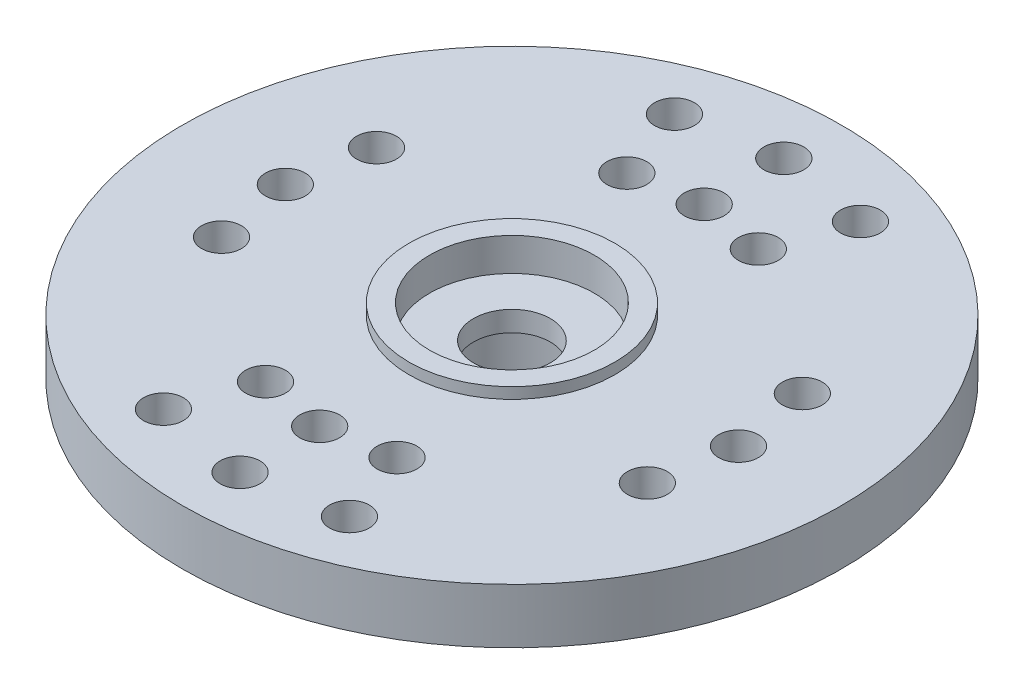
SolidWorks part; units mm, degrees
ref_plane "Front Plane" through (0, 0, 0) normal (0, 0, 1) x (1, 0, 0)
ref_plane "Top Plane" through (0, 0, 0) normal (0, 1, 0) x (1, 0, 0)
ref_plane "Right Plane" through (0, 0, 0) normal (1, 0, 0) x (0, 0, -1)
sketch "Sketch1" plane through (0, 0, 0) normal (0, 0, 1) x (1, 0, 0)
  line L0 (-3.75, 0) -> (-12, 0)
  line L1 (-3.75, 0) -> (-3.75, 0.4)
  line L2 (-3.75, 0.4) -> (-3, 0.4)
  line L3 (-3, 0.4) -> (-3, -0.8)
  line L4 (-3, -0.8) -> (-1.4, -0.8)
  line L5 (-1.4, -0.8) -> (-1.4, -1.54)
  line L6 (-1.4, -1.54) -> (-2.65, -1.54)
  line L7 (-2.65, -1.54) -> (-2.65, -4.54)
  line L8 (-2.65, -4.54) -> (-4.44, -4.54)
  line L9 (-4.44, -4.54) -> (-4.44, -2)
  line L10 (-4.44, -2) -> (-12, -2)
  line L11 (-12, -2) -> (-12, 0)
  line L12 (0, 0) -> (0, -4.54) construction
  dimension "D1" = 12
  dimension "D2" = 2
  dimension "D3" = 3.75
  dimension "D4" = 0.4
  dimension "D5" = 3
  dimension "D6" = 1.2
  dimension "D7" = 2.54
  dimension "D8" = 4.44
  dimension "D9" = 2.65
  dimension "D10" = 3
  dimension "D11" = 1.4
revolve "Revolve1" add sketch "Sketch1" angle 360 about L12
sketch "Sketch2" plane through (0, 0, 0) normal (0, 1, 0) x (1, 0, 0)
  line L0 (-7.7525, 2.8217) -> (0, 0) construction
  line L1 (0, 0) -> (-8.25, 0) construction
  line L2 (0, 7) -> (0, 0) construction
  line L3 (0, 0) -> (2.3941, 6.5778) construction
  circle A0 centre (-8.25, 0) radius 0.725
  circle A1 centre (-7.7525, 2.8217) radius 0.725
  circle A2 centre (0, 7) radius 0.725
  circle A3 centre (0, 9.9) radius 0.725
  circle A4 centre (2.3941, 6.5778) radius 0.725
  circle A5 centre (3.386, 9.303) radius 0.725
  circle A6 centre (-2.3941, 6.5778) radius 0.725
  circle A7 centre (-3.386, 9.303) radius 0.725
  circle A8 centre (-7.7525, -2.8217) radius 0.725
  circle A9 centre (7.7525, -2.8217) radius 0.725
  circle A10 centre (7.7525, 2.8217) radius 0.725
  circle A11 centre (8.25, 0) radius 0.725
  circle A12 centre (2.3941, -6.5778) radius 0.725
  circle A13 centre (3.386, -9.303) radius 0.725
  circle A14 centre (0, -9.9) radius 0.725
  circle A15 centre (0, -7) radius 0.725
  circle A16 centre (-2.3941, -6.5778) radius 0.725
  circle A17 centre (-3.386, -9.303) radius 0.725
  point P8 (0, 0)
  point P12 (10.7603, -2.0477)
  point P19 (0, 0)
  point P25 (0, 0)
  point P26 (0, 0)
  point P44 (0, 0)
  point P45 (8.25, 0)
  point P46 (8.25, 0)
  point P47 (0, 0)
  point P48 (0, 0)
  dimension "D1" = 1.45
  dimension "D2" = 8.25
  dimension "D4" = 20
  dimension "D5" = 7
  dimension "D6" = 9.9
  dimension "D8" = 20
  dimension "D3" = 2
  dimension "D7" = 2
  dimension "D9" = 2
extrude "Cut-Extrude1" cut sketch "Sketch2" against normal through all
